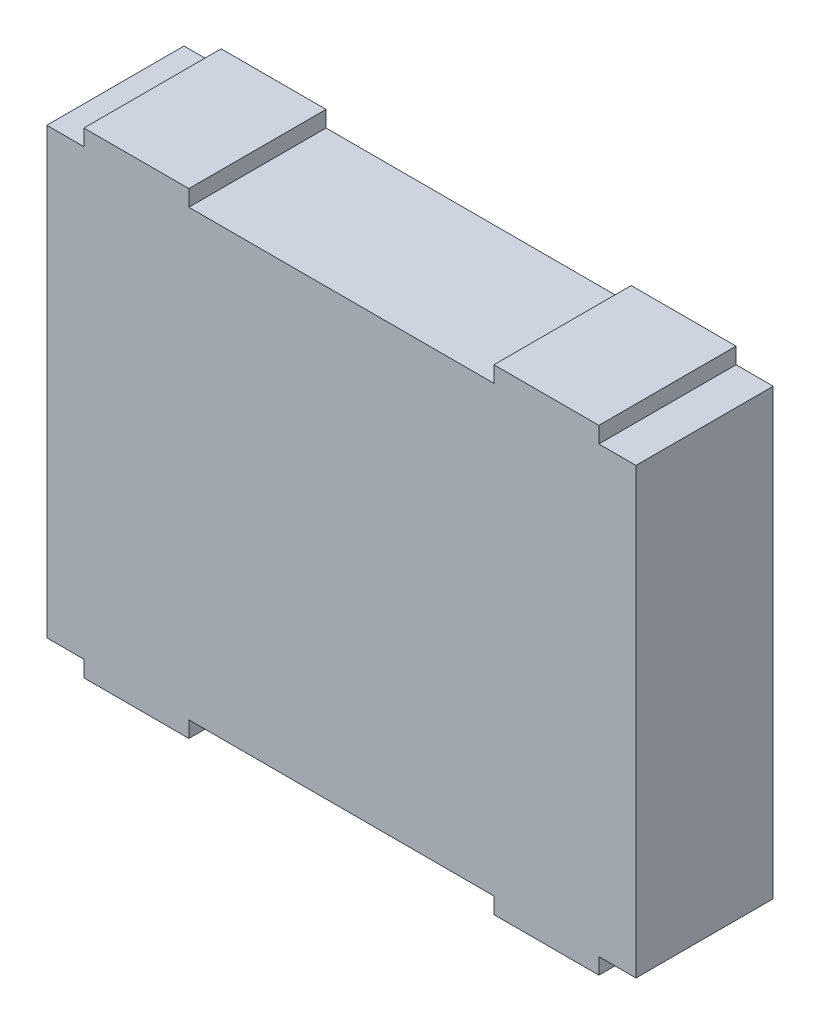
SolidWorks part; units mm, degrees
ref_plane "前视基准面" through (0, 0, 0) normal (0, 0, 1) x (1, 0, 0)
ref_plane "上视基准面" through (0, 0, 0) normal (0, 1, 0) x (1, 0, 0)
ref_plane "右视基准面" through (0, 0, 0) normal (1, 0, 0) x (0, 0, -1)
sketch "草图1" plane through (0, 0, 0) normal (0, 0, 1) x (1, 0, 0)
  line L0 (3.19, 2.95) -> (3.19, 2.75)
  line L1 (3.19, 2.75) -> (3.65, 2.75)
  line L2 (3.65, 2.75) -> (3.65, -2.75)
  line L3 (3.65, -2.75) -> (3.19, -2.75)
  line L4 (3.19, -2.75) -> (3.19, -2.95)
  line L5 (3.19, -2.95) -> (1.89, -2.95)
  line L6 (1.89, -2.95) -> (1.89, -2.75)
  line L7 (1.89, -2.75) -> (-1.89, -2.75)
  line L8 (-1.89, -2.75) -> (-1.89, -2.95)
  line L9 (-1.89, -2.95) -> (-3.19, -2.95)
  line L10 (-3.19, -2.95) -> (-3.19, -2.75)
  line L11 (-3.19, -2.75) -> (-3.65, -2.75)
  line L12 (-3.65, -2.75) -> (-3.65, 2.75)
  line L13 (-3.65, 2.75) -> (-3.19, 2.75)
  line L14 (-3.19, 2.75) -> (-3.19, 2.95)
  line L15 (-3.19, 2.95) -> (-1.89, 2.95)
  line L16 (-1.89, 2.95) -> (-1.89, 2.75)
  line L17 (-1.89, 2.75) -> (1.89, 2.75)
  line L18 (1.89, 2.75) -> (1.89, 2.95)
  line L19 (1.89, 2.95) -> (3.19, 2.95)
extrude "Component_Outline" add sketch "草图1" along normal blind 1.7 separate body
sketch3d "3D草图1"
  line L0 (0, 0, 0) -> (1, 0, 0)
  line L1 (0, 0, 0) -> (0, 1, 0)
  line L2 (0, 0, 0) -> (0, 0, 1)
  point P0 (0, 0, 0)
